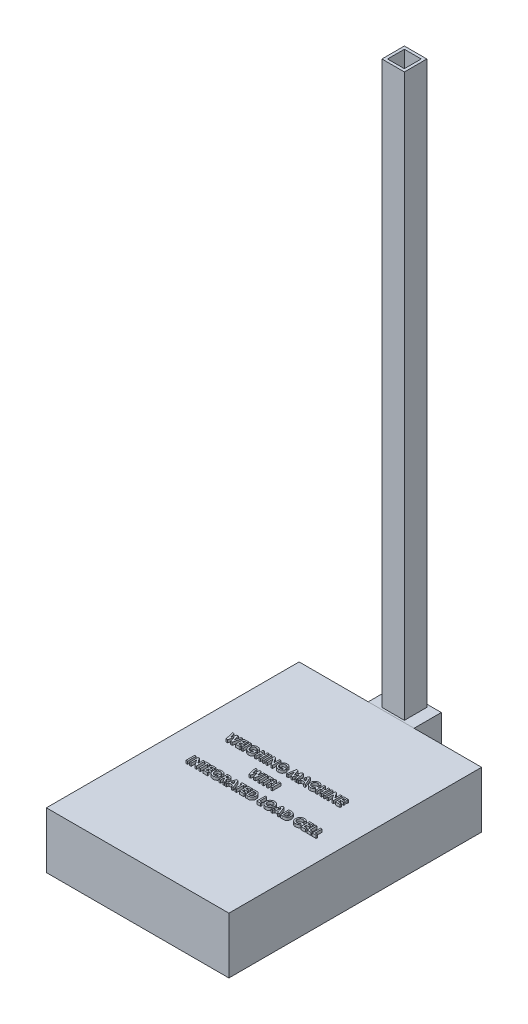
SolidWorks part; units mm, degrees
ref_plane "Front Plane" through (0, 0, 0) normal (0, 0, 1) x (1, 0, 0)
ref_plane "Top Plane" through (0, 0, 0) normal (0, 1, 0) x (1, 0, 0)
ref_plane "Right Plane" through (0, 0, 0) normal (1, 0, 0) x (0, 0, -1)
sketch "Sketch1" plane through (0, 0, 0) normal (0, 1, 0) x (1, 0, 0)
  line L1 (-16.25, 22.5) -> (16.25, 22.5)
  line L2 (-16.25, 22.5) -> (-16.25, -22.5)
  line L3 (-16.25, -22.5) -> (16.25, -22.5)
  line L4 (16.25, 22.5) -> (16.25, -22.5)
  line L5 (-16.25, 22.5) -> (16.25, -22.5) construction
  line L6 (-16.25, -22.5) -> (16.25, 22.5) construction
  point P0 (0, 0)
  point P6 (0, 0)
  dimension "D1" = 32.5
  dimension "D2" = 45
extrude "Boss-Extrude1" add sketch "Sketch1" along normal blind 10
sketch "Sketch2" plane through (0, 10, 0) normal (0, 1, 0) x (1, 0, 0)
  text T0 "<b>WEIGHING MACHINE </b>\r\n<b>             WITH </b>\r\n<b>INTEGRATED LOAD CEL</b>L" font "Century Gothic" height 1.5
extrude "Boss-Extrude2" add sketch "Sketch2" along normal blind 0.5
sketch "Sketch3" plane through (0, 0, -22.5) normal (0, 0, -1) x (-1, 0, 0)
  line L0 (-16.25, 0) -> (16.25, 0) construction
  line L1 (-4.0771, 9.8608) -> (4.0771, 9.8608)
  line L2 (-4.0771, 9.8608) -> (-4.0771, 0)
  line L3 (-4.0771, 0) -> (4.0771, 0)
  line L4 (4.0771, 9.8608) -> (4.0771, 0)
  line L5 (-4.0771, 9.8608) -> (4.0771, 0) construction
  line L6 (-4.0771, 0) -> (4.0771, 9.8608) construction
  point P0 (0, 4.9304)
extrude "Boss-Extrude3" add sketch "Sketch3" along normal blind 5
sketch "Sketch4" plane through (0, 9.8608, 0) normal (0, 1, 0) x (1, 0, 0)
  line L0 (16.25, 22.5) -> (-16.25, 22.5) construction
  line L2 (-2.0021, 23) -> (1.9979, 23)
  line L3 (-2.0021, 23) -> (-2.0021, 27)
  line L4 (-2.0021, 27) -> (1.9979, 27)
  line L5 (1.9979, 23) -> (1.9979, 27)
  line L6 (-2.0021, 23) -> (1.9979, 27) construction
  line L7 (-2.0021, 27) -> (1.9979, 23) construction
  line L8 (-4.0771, 27.5) -> (-4.0771, 22.5) construction
  line L9 (-1.5021, 26.5) -> (1.4979, 26.5)
  line L10 (-1.5021, 26.5) -> (-1.5021, 23.5)
  line L11 (-1.5021, 23.5) -> (1.4979, 23.5)
  line L12 (1.4979, 26.5) -> (1.4979, 23.5)
  line L13 (-1.5021, 26.5) -> (1.4979, 23.5) construction
  line L14 (-1.5021, 23.5) -> (1.4979, 26.5) construction
  point P0 (-0.0021, 23)
  point P1 (-0.0021, 25)
  point P8 (-0.0021, 25)
  dimension "D1" = 4
  dimension "D2" = 4
  dimension "D3" = 4
  dimension "D4" = 0.5
  dimension "D5" = 4.075
  dimension "D6" = 3
  dimension "D7" = 3
extrude "Boss-Extrude4" add sketch "Sketch4" along normal blind 100
